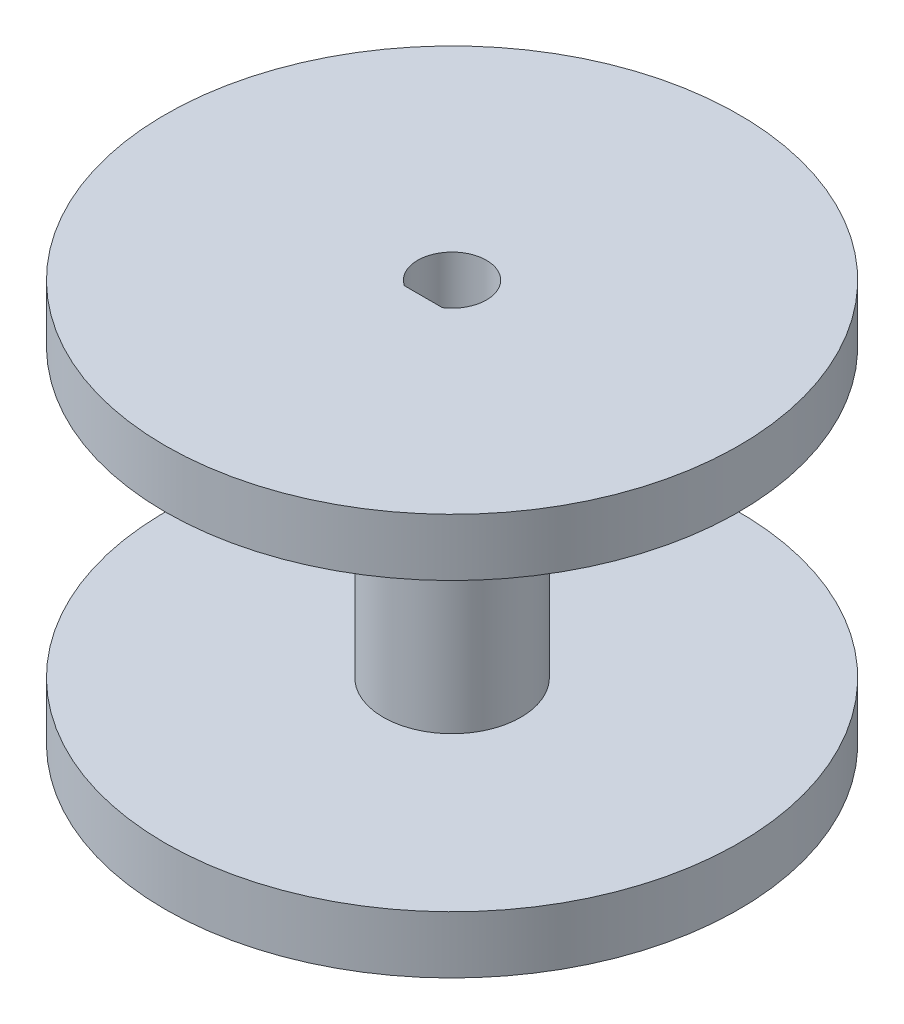
SolidWorks part; units mm, degrees
ref_plane "Front Plane" through (0, 0, 0) normal (0, 0, 1) x (1, 0, 0)
ref_plane "Top Plane" through (0, 0, 0) normal (0, 1, 0) x (1, 0, 0)
ref_plane "Right Plane" through (0, 0, 0) normal (1, 0, 0) x (0, 0, -1)
sketch "Sketch1" plane through (0, 0, 0) normal (0, 1, 0) x (1, 0, 0)
  circle A0 centre (0, 0) radius 25
extrude "Boss-Extrude1" add sketch "Sketch1" along normal blind 5
sketch "Sketch2" plane through (0, 5, 0) normal (0, 1, 0) x (1, 0, 0)
  circle A0 centre (0, 0) radius 6
extrude "Boss-Extrude2" add sketch "Sketch2" along normal blind 25
sketch "Sketch3" plane through (0, 30, 0) normal (0, 1, 0) x (1, 0, 0)
  circle A0 centre (0, 0) radius 25
extrude "Boss-Extrude3" add sketch "Sketch3" along normal blind 5 contours A0
sketch "Sketch4" plane through (0, 35, 0) normal (0, 1, 0) x (1, 0, 0)
  line L1 (0, -2.5) -> (-1.6583, -2.5)
  line L2 (0, -2.5) -> (1.6583, -2.5)
  arc A0 (1.6583, -2.5) -> (-1.6583, -2.5) centre (0, 0) ccw
extrude "Cut-Extrude1" cut sketch "Sketch4" against normal blind 10
